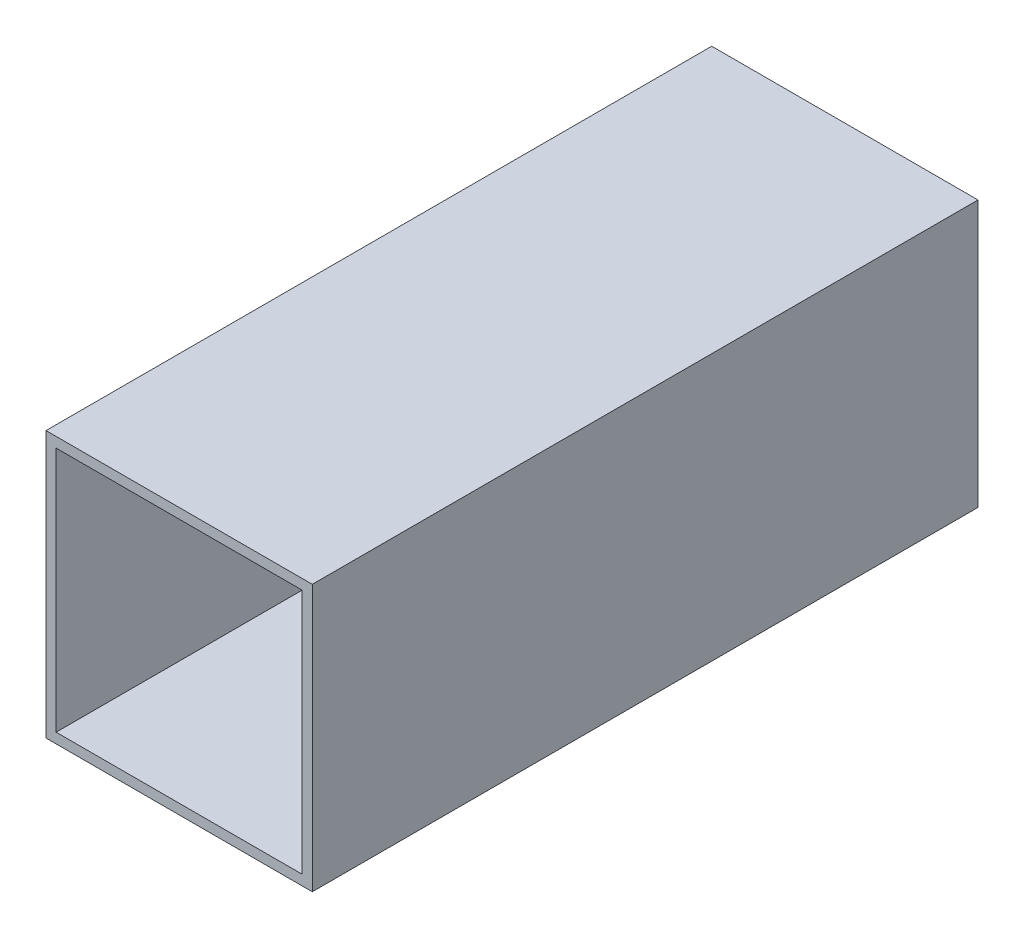
SolidWorks part; units mm, degrees
ref_plane "Alzado" through (0, 0, 0) normal (0, 0, 1) x (1, 0, 0)
ref_plane "Planta" through (0, 0, 0) normal (0, 1, 0) x (1, 0, 0)
ref_plane "Vista lateral" through (0, 0, 0) normal (1, 0, 0) x (0, 0, -1)
sketch "Croquis1" plane through (0, 0, 0) normal (0, 0, 1) x (1, 0, 0)
  line L0 (2.9, -2.9) -> (73.3, -2.9)
  line L1 (0, 0) -> (76.2, 0)
  line L2 (0, 0) -> (0, -76.2)
  line L3 (0, -76.2) -> (76.2, -76.2)
  line L4 (76.2, 0) -> (76.2, -76.2)
  line L5 (73.3, -2.9) -> (73.3, -73.3)
  line L6 (2.9, -73.3) -> (73.3, -73.3)
  line L7 (2.9, -2.9) -> (2.9, -73.3)
  dimension "D1" = 76.2
  dimension "D2" = 76.2
  dimension "D3" = 2.9
extrude "Saliente-Extruir1" add sketch "Croquis1" along normal blind 190.5
